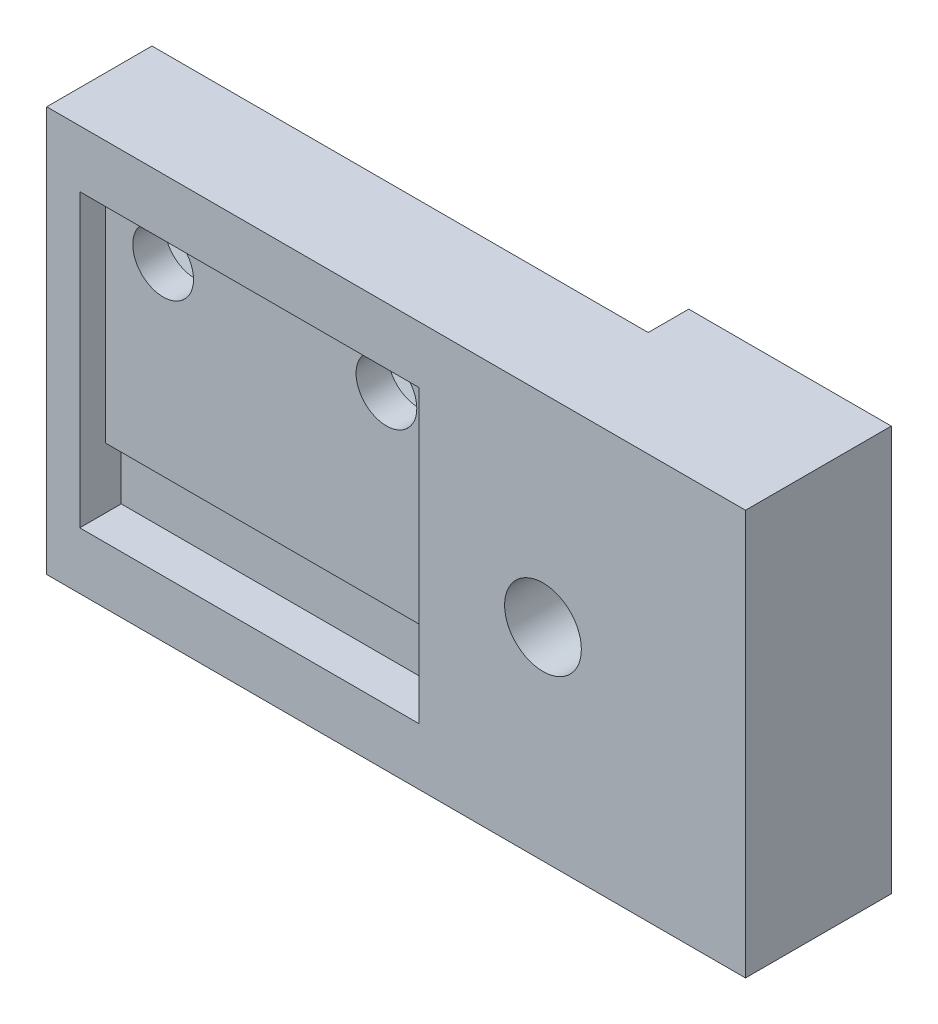
SolidWorks part; units mm, degrees
ref_plane "Front Plane" through (0, 0, 0) normal (0, 0, 1) x (1, 0, 0)
ref_plane "Top Plane" through (0, 0, 0) normal (0, 1, 0) x (1, 0, 0)
ref_plane "Right Plane" through (0, 0, 0) normal (1, 0, 0) x (0, 0, -1)
sketch "Sketch1" plane through (0, 0, 0) normal (0, 0, 1) x (1, 0, 0)
  line L0 (19.7, 12.7) -> (31.115, 12.7) construction
  line L1 (0, 0) -> (43.815, 0)
  line L2 (0, 0) -> (0, 25.4)
  line L3 (0, 25.4) -> (43.815, 25.4)
  line L4 (43.815, 0) -> (43.815, 25.4)
  line L5 (5.7, 19.026) -> (19.7, 19.026) construction
  line L6 (5.7, 19.026) -> (5.7, 6.374) construction
  line L7 (5.7, 6.374) -> (19.7, 6.374) construction
  line L8 (19.7, 19.026) -> (19.7, 6.374) construction
  line L9 (12.7, 19.026) -> (12.7, 25.4) construction
  line L10 (12.7, 6.374) -> (12.7, 0) construction
  line L11 (1.27, 24.13) -> (1.27, 25.4) construction
  line L12 (24.13, 1.27) -> (1.27, 1.27) construction
  line L13 (24.13, 1.27) -> (24.13, 24.13) construction
  line L14 (24.13, 24.13) -> (1.27, 24.13) construction
  line L15 (1.27, 1.27) -> (1.27, 24.13) construction
  line L16 (24.13, 1.27) -> (1.27, 24.13) construction
  line L17 (24.13, 24.13) -> (1.27, 1.27) construction
  line L18 (1.27, 24.13) -> (0, 24.13) construction
  circle A0 centre (5.7, 19.026) radius 1.904
  circle A1 centre (19.7, 19.026) radius 1.904
  circle A2 centre (19.7, 6.374) radius 1.904 construction
  circle A3 centre (5.7, 6.374) radius 1.904 construction
  circle A4 centre (31.115, 12.7) radius 2.4067
  point P20 (12.7, 12.7)
  dimension "D1" = 4.8133
  dimension "D2" = 3.808
  dimension "D3" = 12.652
  dimension "D4" = 14
  dimension "D5" = 25.4
  dimension "D6" = 22.86
  dimension "D7" = 1.27
  dimension "D8" = 6.985
  dimension "D9" = 12.7
extrude "Boss-Extrude1" add sketch "Sketch1" along normal blind 2
sketch "Sketch2" plane through (0, 0, 2) normal (0, 0, 1) x (1, 0, 0)
  line L0 (5.7, 19.026) -> (19.7, 19.026) construction
  line L1 (12.7, 19.026) -> (12.7, 12.7) construction
  line L3 (2.073, 3.573) -> (23.327, 3.573)
  line L4 (0, 25.4) -> (0, 0)
  line L5 (0, 0) -> (43.815, 0)
  line L6 (43.815, 0) -> (43.815, 25.4)
  line L7 (43.815, 25.4) -> (0, 25.4)
  line L8 (0, 25.4) -> (0, 0)
  line L9 (0, 0) -> (43.815, 0)
  line L10 (43.815, 0) -> (43.815, 25.4)
  line L11 (43.815, 25.4) -> (0, 25.4)
  line L12 (2.073, 3.573) -> (2.073, 21.827)
  line L13 (2.073, 21.827) -> (23.327, 21.827)
  line L14 (23.327, 3.573) -> (23.327, 21.827)
  line L15 (2.073, 3.573) -> (23.327, 21.827) construction
  line L16 (2.073, 21.827) -> (23.327, 3.573) construction
  circle A0 centre (31.115, 12.7) radius 2.4067 construction
  circle A1 centre (31.115, 12.7) radius 2.4067
  point P12 (12.7, 12.7)
  point P13 (12.7, 12.7)
  point P21 (0, 0)
  point P22 (0, 0)
  dimension "D2" = 21.254
  dimension "D3" = 18.254
  dimension "D4" = 2.801
  dimension "D1" = 0
extrude "Boss-Extrude2" add sketch "Sketch2" along normal blind 1.6
sketch "Sketch3" plane through (0, 0, 0) normal (0, 0, -1) x (-1, 0, 0)
  line L1 (-16.569, 17.2183) -> (-16.569, 20.8337)
  line L2 (-16.569, 20.8337) -> (-19.7, 22.6414)
  line L3 (-19.7, 22.6414) -> (-22.831, 20.8337)
  line L4 (0, 0) -> (0, 25.4)
  line L5 (0, 25.4) -> (-43.815, 25.4)
  line L6 (-43.815, 25.4) -> (-43.815, 0)
  line L7 (-43.815, 0) -> (0, 0)
  line L8 (0, 0) -> (0, 25.4)
  line L9 (0, 25.4) -> (-43.815, 25.4)
  line L10 (-43.815, 25.4) -> (-43.815, 0)
  line L11 (-43.815, 0) -> (0, 0)
  line L12 (-22.831, 20.8337) -> (-22.831, 17.2183)
  line L13 (-22.831, 17.2183) -> (-19.7, 15.4106)
  line L14 (-19.7, 15.4106) -> (-16.569, 17.2183)
  line L15 (-2.569, 20.8337) -> (-5.7, 22.6414)
  line L16 (-5.7, 22.6414) -> (-8.831, 20.8337)
  line L17 (-8.831, 20.8337) -> (-8.831, 17.2183)
  line L18 (-8.831, 17.2183) -> (-5.7, 15.4106)
  line L19 (-5.7, 15.4106) -> (-2.569, 17.2183)
  line L20 (-2.569, 17.2183) -> (-2.569, 20.8337)
  circle A0 centre (-31.115, 12.7) radius 2.4067 construction
  circle A1 centre (-31.115, 12.7) radius 2.4067
  circle A2 centre (-19.7, 19.026) radius 3.131 construction
  circle A3 centre (-5.7, 19.026) radius 3.131 construction
  circle A6 centre (-5.7, 19.026) radius 1.904 construction
  dimension "D2" = 6.262
  dimension "D1" = 0
extrude "Boss-Extrude3" add sketch "Sketch3" along normal blind 3
sketch "Sketch4" plane through (0, 0, -3) normal (0, 0, -1) x (-1, 0, 0)
  line L0 (-31.115, 25.4) -> (-31.115, 21.717)
  line L2 (-31.115, 21.717) -> (-32.6152, 21.717)
  line L3 (-31.115, 25.4) -> (-43.815, 25.4)
  line L4 (-43.815, 25.4) -> (-43.815, 0)
  line L5 (-43.815, 0) -> (-31.115, 0)
  line L7 (-31.115, 0) -> (-31.115, 3.683)
  line L8 (-31.115, 3.683) -> (-32.6152, 3.683)
  line L9 (-40.132, 14.2002) -> (-40.132, 11.1998)
  line L10 (-31.115, 12.7) -> (-32.8168, 10.9982) construction
  line L11 (-43.815, 0) -> (0, 0) construction
  line L12 (-43.815, 25.4) -> (-43.815, 0) construction
  line L13 (0, 25.4) -> (-43.815, 25.4) construction
  arc A0 (-32.6152, 21.717) -> (-40.132, 14.2002) centre (-32.6152, 14.2002) ccw
  arc A1 (-40.132, 11.1998) -> (-32.6152, 3.683) centre (-32.6152, 11.1998) ccw
  circle A3 centre (-31.115, 12.7) radius 2.4067 construction
  point P0 (-31.115, 12.7)
  point P6 (-32.6985, 10.8877)
  point P21 (0, 0)
  point P26 (-37.9304, 5.8846)
  point P27 (0, 0)
  point P28 (0, 0)
  point P29 (0, 0)
  dimension "D1" = 18.034
  dimension "D4" = 45
extrude "Boss-Extrude4" add sketch "Sketch4" along normal blind 2.54
sketch "Sketch5" plane through (0, 0, 2) normal (0, 0, 1) x (1, 0, 0)
  line L0 (2.073, 21.827) -> (2.073, 3.573) construction
  line L1 (2.073, 7.383) -> (23.327, 7.383)
  line L2 (2.073, 7.383) -> (2.073, 3.573)
  line L3 (2.073, 3.573) -> (23.327, 3.573)
  line L4 (23.327, 7.383) -> (23.327, 3.573)
  dimension "D1" = 3.81
extrude "Cut-Extrude1" cut sketch "Sketch5" against normal blind 1
